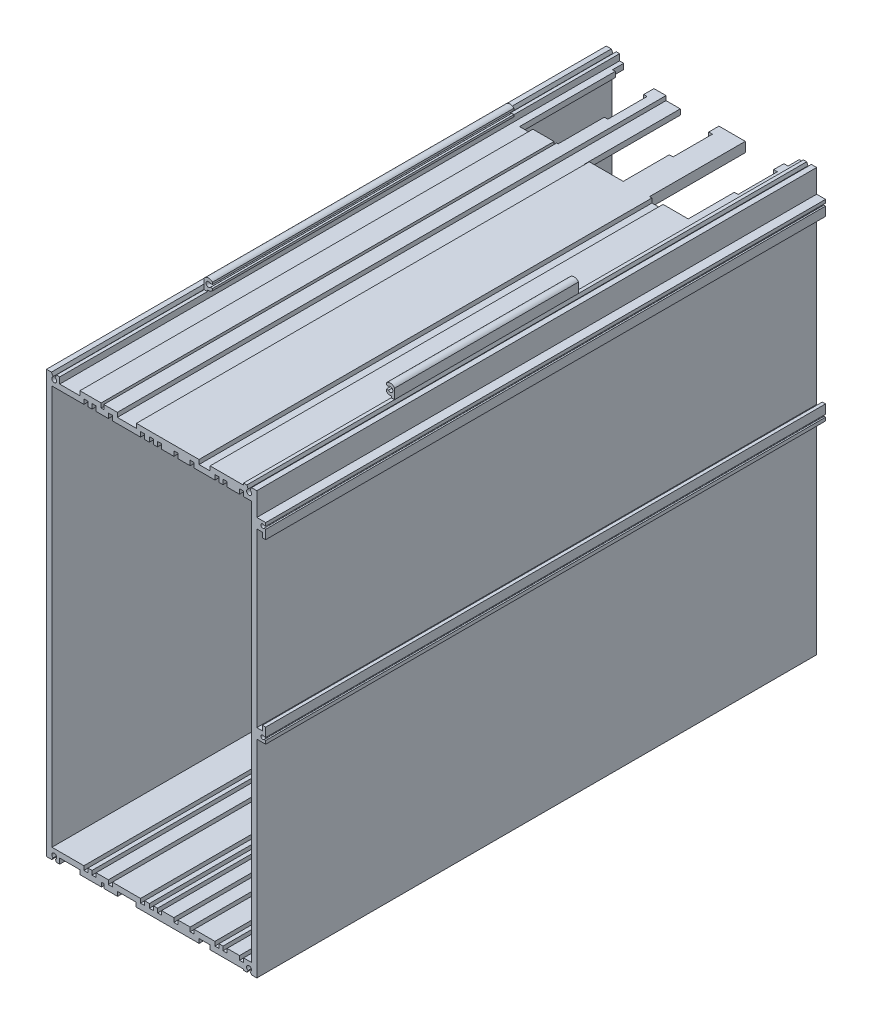
SolidWorks part; units mm, degrees
ref_plane "Front Plane" through (0, 0, 0) normal (0, 0, 1) x (1, 0, 0)
ref_plane "Top Plane" through (0, 0, 0) normal (0, 1, 0) x (1, 0, 0)
ref_plane "Right Plane" through (0, 0, 0) normal (1, 0, 0) x (0, 0, -1)
sketch "Sketch2" plane through (0, 0, 0) normal (0, 0, 1) x (1, 0, 0)
  line L0 (23.2732, 131.1707) -> (119.1108, 131.6725) construction
  line L1 (14.5, 261.3734) -> (14.5, 257.5858)
  line L2 (14.5, 257.5858) -> (26.7, 257.5858)
  line L3 (26.7, 257.5858) -> (26.7, 260.24)
  line L4 (26.7, 260.24) -> (39.5, 260.24)
  line L5 (39.5, 260.24) -> (39.5, 257.5858)
  line L6 (39.5, 257.5858) -> (41.1, 257.5858)
  line L7 (41.1, 257.5858) -> (41.1, 260.24)
  line L8 (41.1, 260.24) -> (49.3, 260.24)
  line L9 (49.3, 260.24) -> (49.3, 257.5858)
  line L10 (49.3, 257.5858) -> (60.8, 257.5858)
  line L11 (60.8, 257.5858) -> (60.8, 260.24)
  line L12 (60.8, 260.24) -> (98.6, 260.24)
  line L13 (98.6, 260.24) -> (98.6, 257.5858)
  line L14 (98.6, 257.5858) -> (105.3, 257.5858)
  line L15 (105.3, 257.5858) -> (105.3, 260.24)
  line L16 (105.3, 260.24) -> (125.5, 260.24)
  line L17 (125.5, 260.24) -> (125.5, 261.3734)
  line L18 (125.5, 261.3734) -> (127.5, 261.3734)
  line L19 (133.5, 261.3734) -> (133.5, 247.3734)
  line L20 (133.5, 247.3734) -> (138.85, 247.3734)
  line L21 (138.85, 247.3734) -> (138.85, 238.4234)
  line L22 (138.85, 238.4234) -> (136.9, 238.4234)
  line L23 (136.9, 238.4234) -> (136.9, 241.3734)
  line L24 (136.9, 241.3734) -> (133.5, 241.3734)
  line L25 (133.5, 241.3734) -> (133.5, 137.4734)
  line L26 (133.5, 137.4734) -> (136.9, 137.4734)
  line L27 (136.9, 137.4734) -> (136.9, 140.4234)
  line L28 (136.9, 140.4234) -> (138.85, 140.4234)
  line L29 (138.85, 140.4234) -> (138.85, 131.4734)
  line L30 (138.85, 131.4734) -> (133.5, 131.4734)
  line L31 (133.5, 131.4734) -> (133.5, 6.5734)
  line L32 (133.5, 6.5734) -> (130.3, 6.5734)
  line L33 (125.5, 6.5734) -> (125.5, 7.202)
  line L34 (125.5, 7.202) -> (105.25, 7.202)
  line L35 (105.25, 7.202) -> (105.25, 9.7858)
  line L36 (105.25, 9.7858) -> (98.65, 9.7858)
  line L37 (98.65, 9.7858) -> (98.65, 7.202)
  line L38 (98.65, 7.202) -> (60.55, 7.202)
  line L39 (60.55, 7.202) -> (60.55, 9.7858)
  line L40 (60.55, 9.7858) -> (49.45, 9.7858)
  line L41 (49.45, 9.7858) -> (49.45, 7.202)
  line L42 (49.45, 7.202) -> (41.2, 7.202)
  line L43 (41.2, 7.202) -> (41.2, 9.7858)
  line L44 (41.2, 9.7858) -> (39.6964, 9.7858)
  line L45 (39.6964, 9.7858) -> (39.6964, 7.202)
  line L46 (39.6964, 7.202) -> (26.5964, 7.202)
  line L47 (26.5964, 7.202) -> (26.5964, 9.7858)
  line L48 (26.5964, 9.7858) -> (14.4964, 9.7858)
  line L49 (14.4964, 9.7858) -> (14.4964, 6.5734)
  line L50 (14.4964, 6.5734) -> (12.4964, 6.5734)
  line L51 (6.5, 6.5734) -> (6.5, 261.3734)
  line L52 (6.5, 261.3734) -> (9.5, 261.3734)
  line L53 (9.8, 254.2858) -> (29.1, 254.2858)
  line L54 (29.1, 254.2858) -> (29.1, 257.1858)
  line L55 (29.1, 257.1858) -> (31.55, 257.1858)
  line L56 (31.55, 257.1858) -> (31.55, 254.2858)
  line L57 (31.55, 254.2858) -> (34, 254.2858)
  line L58 (34, 254.2858) -> (34, 257.1858)
  line L59 (34, 257.1858) -> (36.45, 257.1858)
  line L60 (36.45, 257.1858) -> (36.45, 254.2858)
  line L61 (36.45, 254.2858) -> (43.85, 254.2858)
  line L62 (43.85, 254.2858) -> (43.85, 257.1858)
  line L63 (43.85, 257.1858) -> (46.3, 257.1858)
  line L64 (46.3, 257.1858) -> (46.3, 254.2858)
  line L65 (46.3, 254.2858) -> (63.3, 254.2858)
  line L66 (63.3, 254.2858) -> (63.3, 257.1858)
  line L67 (63.3, 257.1858) -> (65.75, 257.1858)
  line L68 (65.75, 257.1858) -> (65.75, 254.2858)
  line L69 (65.75, 254.2858) -> (68.65, 254.2858)
  line L70 (68.65, 254.2858) -> (68.65, 257.1858)
  line L71 (68.65, 257.1858) -> (71.1, 257.1858)
  line L72 (71.1, 257.1858) -> (71.1, 254.2858)
  line L73 (71.1, 254.2858) -> (73.55, 254.2858)
  line L74 (73.55, 254.2858) -> (73.55, 257.1858)
  line L75 (73.55, 257.1858) -> (76, 257.1858)
  line L76 (76, 257.1858) -> (76, 254.2858)
  line L77 (76, 254.2858) -> (83.4, 254.2858)
  line L78 (83.4, 254.2858) -> (83.4, 257.1858)
  line L79 (83.4, 257.1858) -> (85.85, 257.1858)
  line L80 (85.85, 257.1858) -> (85.85, 254.2858)
  line L81 (85.85, 254.2858) -> (93.25, 254.2858)
  line L82 (93.25, 254.2858) -> (93.25, 257.1858)
  line L83 (93.25, 257.1858) -> (95.7, 257.1858)
  line L84 (95.7, 257.1858) -> (95.7, 254.2858)
  line L85 (95.7, 254.2858) -> (108.2, 254.2858)
  line L86 (108.2, 254.2858) -> (108.2, 257.1858)
  line L87 (108.2, 257.1858) -> (110.65, 257.1858)
  line L88 (110.65, 257.1858) -> (110.65, 254.2858)
  line L89 (110.65, 254.2858) -> (113.1, 254.2858)
  line L90 (113.1, 254.2858) -> (113.1, 257.1858)
  line L91 (113.1, 257.1858) -> (115.55, 257.1858)
  line L92 (115.55, 257.1858) -> (115.55, 254.2858)
  line L93 (115.55, 254.2858) -> (123.05, 254.2858)
  line L94 (123.05, 254.2858) -> (123.05, 257.1858)
  line L95 (123.05, 257.1858) -> (125.5, 257.1858)
  line L96 (125.5, 257.1858) -> (125.5, 254.2858)
  line L97 (125.5, 254.2858) -> (130.2, 254.2858)
  line L98 (130.2, 254.2858) -> (130.2, 13.0858)
  line L99 (130.2, 13.0858) -> (125.5, 13.0858)
  line L100 (125.5, 13.0858) -> (125.5, 10.6056)
  line L101 (125.5, 10.6056) -> (123.05, 10.6056)
  line L102 (123.05, 10.6056) -> (123.05, 13.0858)
  line L103 (123.05, 13.0858) -> (115.55, 13.0858)
  line L104 (115.55, 13.0858) -> (115.55, 10.6056)
  line L105 (115.55, 10.6056) -> (113.1, 10.6056)
  line L106 (113.1, 10.6056) -> (113.1, 13.0858)
  line L107 (113.1, 13.0858) -> (110.65, 13.0858)
  line L108 (110.65, 13.0858) -> (110.65, 10.6056)
  line L109 (110.65, 10.6056) -> (108.2, 10.6056)
  line L110 (108.2, 10.6056) -> (108.2, 13.0858)
  line L111 (108.2, 13.0858) -> (95.7, 13.0858)
  line L112 (95.7, 13.0858) -> (95.7, 10.6056)
  line L113 (95.7, 10.6056) -> (93.25, 10.6056)
  line L114 (93.25, 10.6056) -> (93.25, 13.0858)
  line L115 (93.25, 13.0858) -> (85.85, 13.0858)
  line L116 (85.85, 13.0858) -> (85.85, 10.6056)
  line L117 (85.85, 10.6056) -> (83.4, 10.6056)
  line L118 (83.4, 10.6056) -> (83.4, 13.0858)
  line L119 (83.4, 13.0858) -> (76, 13.0858)
  line L120 (76, 13.0858) -> (76, 10.6056)
  line L121 (76, 10.6056) -> (73.55, 10.6056)
  line L122 (73.55, 10.6056) -> (73.55, 13.0858)
  line L123 (73.55, 13.0858) -> (71.1, 13.0858)
  line L124 (71.1, 13.0858) -> (71.1, 10.6056)
  line L125 (71.1, 10.6056) -> (68.65, 10.6056)
  line L126 (68.65, 10.6056) -> (68.65, 13.0858)
  line L127 (68.65, 13.0858) -> (65.75, 13.0858)
  line L128 (65.75, 13.0858) -> (65.75, 10.6056)
  line L129 (65.75, 10.6056) -> (63.3, 10.6056)
  line L130 (63.3, 10.6056) -> (63.3, 13.0858)
  line L131 (63.3, 13.0858) -> (46.3, 13.0858)
  line L132 (46.3, 13.0858) -> (46.3, 10.6056)
  line L133 (46.3, 10.6056) -> (43.85, 10.6056)
  line L134 (43.85, 10.6056) -> (43.85, 13.0858)
  line L135 (43.85, 13.0858) -> (36.45, 13.0858)
  line L136 (36.45, 13.0858) -> (36.45, 10.6056)
  line L137 (36.45, 10.6056) -> (34, 10.6056)
  line L138 (34, 10.6056) -> (34, 13.0858)
  line L139 (34, 13.0858) -> (31.55, 13.0858)
  line L140 (31.55, 13.0858) -> (31.55, 10.6056)
  line L141 (31.55, 10.6056) -> (29.1, 10.6056)
  line L142 (29.1, 10.6056) -> (29.1, 13.0858)
  line L143 (29.1, 13.0858) -> (9.8, 13.0858)
  line L144 (9.8, 13.0858) -> (9.8, 254.2858)
  line L145 (11.2, 258.1858) -> (12.5, 261.3734)
  line L146 (11.2, 258.1858) -> (9.5, 261.3734)
  line L147 (12.5, 261.3734) -> (14.5, 261.3734)
  line L148 (128.8, 258.1858) -> (127.5, 261.3734)
  line L149 (128.8, 258.1858) -> (130.3, 261.3734)
  line L150 (130.3, 261.3734) -> (133.5, 261.3734)
  line L151 (138.85, 245.3734) -> (137.9352, 245.3734)
  line L152 (138.85, 243.8734) -> (137.8905, 243.8734)
  line L153 (138.85, 133.4734) -> (137.9352, 133.4734)
  line L154 (138.85, 134.9734) -> (137.8905, 134.9734)
  line L155 (128.8, 9.1858) -> (130.3, 6.5734)
  line L156 (128.8, 9.1858) -> (127.5, 6.5734)
  line L157 (127.5, 6.5734) -> (125.5, 6.5734)
  line L158 (11.2, 9.1858) -> (12.4964, 6.5734)
  line L159 (11.2, 9.1858) -> (9.7, 6.5734)
  line L160 (9.7, 6.5734) -> (6.5, 6.5734)
  circle A1 centre (11.2, 258.1858) radius 1.5
  circle A2 centre (128.8, 258.1858) radius 1.5
  circle A3 centre (137.075, 244.6484) radius 1.125
  circle A4 centre (137.075, 134.1984) radius 1.125
  circle A5 centre (128.8, 9.1858) radius 1.5
  circle A6 centre (11.2, 9.1858) radius 1.5
  point P51 (54.8, 13.0858)
  dimension "D1" = 127
  dimension "D87" = 3.2
  dimension "D90" = 3
  dimension "D92" = 2.4
  dimension "D93" = 3
  dimension "D97" = 5.75
  dimension "D101" = 5.75
  dimension "D106" = 3
  dimension "D111" = 3
  dimension "D2" = 3.3
  dimension "D3" = 3.3
  dimension "D4" = 120.4
  dimension "D5" = 8
  dimension "D6" = 8
  dimension "D7" = 3.3
  dimension "D8" = 3.3
  dimension "D9" = 254.8
  dimension "D10" = 247.8
  dimension "D11" = 241.2
  dimension "D12" = 12.2
  dimension "D13" = 12.8
  dimension "D14" = 1.6
  dimension "D15" = 37.8
  dimension "D16" = 8.2
  dimension "D17" = 11.5
  dimension "D18" = 6.7
  dimension "D19" = 20.2
  dimension "D20" = 19.3
  dimension "D21" = 2.9
  dimension "D22" = 2.45
  dimension "D23" = 2.45
  dimension "D24" = 2.45
  dimension "D25" = 2.45
  dimension "D26" = 2.45
  dimension "D27" = 2.45
  dimension "D28" = 2.45
  dimension "D29" = 2.45
  dimension "D30" = 2.45
  dimension "D31" = 2.45
  dimension "D32" = 2.45
  dimension "D33" = 2.45
  dimension "D34" = 7.4
  dimension "D35" = 17
  dimension "D36" = 19.3
  dimension "D37" = 2.9
  dimension "D38" = 2.45
  dimension "D39" = 7.4
  dimension "D40" = 7.4
  dimension "D41" = 12.5
  dimension "D42" = 2.45
  dimension "D43" = 7.5
  dimension "D44" = 4.7
  dimension "D45" = 2.45
  dimension "D46" = 2.45
  dimension "D47" = 2.45
  dimension "D48" = 7.4
  dimension "D49" = 2.45
  dimension "D50" = 17
  dimension "D51" = 2.45
  dimension "D52" = 2.9
  dimension "D53" = 2.45
  dimension "D54" = 2.45
  dimension "D55" = 2.45
  dimension "D56" = 7.4
  dimension "D57" = 2.45
  dimension "D58" = 7.4
  dimension "D59" = 2.45
  dimension "D60" = 12.5
  dimension "D61" = 2.45
  dimension "D62" = 2.45
  dimension "D63" = 2.45
  dimension "D64" = 7.5
  dimension "D65" = 2.45
  dimension "D66" = 4.7
  dimension "D67" = 7.9964
  dimension "D68" = 12.1
  dimension "D69" = 13.1
  dimension "D70" = 8.25
  dimension "D71" = 11.1
  dimension "D72" = 38.1
  dimension "D73" = 6.6
  dimension "D74" = 20.25
  dimension "D75" = 8
  dimension "D76" = 14
  dimension "D77" = 6
  dimension "D78" = 8.95
  dimension "D79" = 3.4
  dimension "D80" = 1.95
  dimension "D81" = 6
  dimension "D82" = 8.95
  dimension "D83" = 3.4
  dimension "D84" = 1.95
  dimension "D85" = 5.35
  dimension "D86" = 103.9
  dimension "D88" = 2.4
  dimension "D89" = 3
  dimension "D91" = 2
  dimension "D94" = 3.2
  dimension "D95" = 2
  dimension "D96" = 3.2
  dimension "D98" = 1.6
  dimension "D99" = 2
  dimension "D100" = 5.45
  dimension "D102" = 1.6
  dimension "D103" = 2
  dimension "D104" = 5.45
  dimension "D105" = 1.5
  dimension "D107" = 2.4
  dimension "D108" = 3.2
  dimension "D109" = 2
  dimension "D110" = 3.2
  dimension "D112" = 2.4
  dimension "D113" = 3.2
  dimension "D114" = 3.2
  dimension "D115" = 2
extrude "Boss-Extrude1" add sketch "Sketch2" along normal blind 338 contours A6 L158 L50 L49 L48 L47 L46 L45 L44 L43 L42 L41 L40 L39 L38 L37 L36 L35 L34 L33 L157 L156 A5 L155 L32 L31 L30 L29 L153 A4 L154 L28 L27 L26 L25 L24 L23 L22 L21 L152 A3 L151 L20 L19 L150 L149 A2 L148 L18
ref_plane "Plane1" through (0, 0, 60) normal (0, 0, -1) x (-1, 0, 0)
sketch "Sketch3" plane through (0, 0, 60) normal (0, 0, -1) x (-1, 0, 0)
  line L0 (-127.5, 261.3734) -> (-127.5, 267.3734)
  line L1 (-122.5, 270.1784) -> (-122.5, 262.1784)
  line L2 (-125.5, 261.3734) -> (-125.5, 269.0865)
  line L3 (-121.7757, 266.54) -> (-123.9222, 266.54)
  line L4 (-121.7757, 264.44) -> (-123.7503, 264.44)
  line L5 (-133.5, 251.3903) -> (-6.5, 251.3903) construction
  line L6 (-133.5, 261.3734) -> (-133.5, 247.3734) construction
  line L7 (-6.5, 6.5734) -> (-6.5, 261.3734) construction
  line L8 (-105.3, 260.24) -> (-125.5, 260.24) construction
  line L10 (-70, 251.3903) -> (-70, 270.1784) construction
  line L11 (-14.5, 261.3734) -> (-14.5, 269.0865)
  line L12 (-12.5, 261.3734) -> (-12.5, 267.3734)
  line L13 (-18.2243, 264.44) -> (-16.2497, 264.44)
  line L14 (-18.2243, 266.54) -> (-16.0778, 266.54)
  line L15 (-17.5, 270.1784) -> (-17.5, 262.1784)
  line L16 (-127.5, 261.3734) -> (-125.5, 261.3734)
  line L17 (-14.5, 261.3734) -> (-12.5, 261.3734)
  circle A0 centre (-124.8514, 265.49) radius 3.25
  circle A2 centre (-124.9004, 265.4028) radius 1.5
  circle A6 centre (-15.0996, 265.4028) radius 1.5
  circle A7 centre (-15.1486, 265.49) radius 3.25
  dimension "D1" = 6.5
  dimension "D5" = 3
  dimension "D6" = 1.85
  dimension "D2" = 5
  dimension "D3" = 6
  dimension "D4" = 2
  dimension "D7" = 2.2
  dimension "D8" = 2.2
extrude "Boss-Extrude2" add sketch "Sketch3" against normal blind 188.8 contours A7 L11 A6 L13 L15 | A7 L12 L11 A6 | L12 A7 L11 L17 | A7 L15 L14 A6 L11 | A0 L0 L16 L2 | A2 L2 A0 L0 | A2 L3 L1 A0 L2 | A2 L2 A0 L1 L4
sketch "Sketch4" plane through (127.5, 0, 0) normal (1, 0, 0) x (0, 0, -1)
  line L0 (-248.8, 261.3734) -> (-248.8, 267.3734) construction
  line L5 (-60, 261.3734) -> (-137.8, 261.3734)
  line L6 (-60, 261.3734) -> (-60, 282.1971)
  line L7 (-60, 282.1971) -> (-137.8, 282.1971)
  line L8 (-137.8, 261.3734) -> (-137.8, 282.1971)
  line L9 (-60, 261.3734) -> (-137.8, 282.1971) construction
  line L10 (-60, 282.1971) -> (-137.8, 261.3734) construction
  point P4 (-98.9, 271.7852)
  dimension "D1" = 111
extrude "Cut-Extrude3" cut sketch "Sketch4" against normal up to next
sketch "Sketch5" plane through (0, 260.24, 0) normal (0, 1, 0) x (1, 0, 0)
  line L0 (105.3, 0) -> (125.5, 0) construction
  line L1 (17, -6.75) -> (123, -6.75)
  line L2 (17, -6.75) -> (17, 0)
  line L3 (17, 0) -> (123, 0)
  line L4 (123, -6.75) -> (123, 0)
  line L5 (17, -6.75) -> (123, 0) construction
  line L6 (17, 0) -> (123, -6.75) construction
  line L7 (14.5, -60) -> (14.5, 0) construction
  line L8 (125.5, -137.8) -> (125.5, 0) construction
  point P4 (70, -3.375)
  dimension "D1" = 106
  dimension "D2" = 2.5
  dimension "D3" = 6.75
  dimension "D4" = 2.5
extrude "Cut-Extrude4" cut sketch "Sketch5" against normal up to next
sketch "Sketch6" plane through (0, 260.24, 0) normal (0, 1, 0) x (1, 0, 0)
  line L0 (105.3, -6.75) -> (123, -6.75) construction
  line L1 (120.5, -6.75) -> (97.15, -6.75)
  line L2 (120.5, -6.75) -> (120.5, -64.55)
  line L3 (120.5, -64.55) -> (97.15, -64.55)
  line L4 (97.15, -6.75) -> (97.15, -64.55)
  line L5 (120.5, -6.75) -> (97.15, -64.55) construction
  line L6 (120.5, -64.55) -> (97.15, -6.75) construction
  line L7 (125.5, -338) -> (125.5, 0) construction
  line L8 (133.5, 0) -> (138.85, 0) construction
  line L9 (60.8, -6.75) -> (98.6, -6.75) construction
  line L10 (81.25, -6.75) -> (57.9, -6.75)
  line L11 (81.25, -6.75) -> (81.25, -64.55)
  line L12 (81.25, -64.55) -> (57.9, -64.55)
  line L13 (57.9, -6.75) -> (57.9, -64.55)
  line L14 (81.25, -6.75) -> (57.9, -64.55) construction
  line L15 (81.25, -64.55) -> (57.9, -6.75) construction
  line L16 (60.8, -6.75) -> (49.3, -6.75) construction
  line L17 (42, -6.75) -> (18.65, -6.75)
  line L18 (42, -6.75) -> (42, -64.55)
  line L19 (42, -64.55) -> (18.65, -64.55)
  line L20 (18.65, -6.75) -> (18.65, -64.55)
  line L21 (42, -6.75) -> (18.65, -64.55) construction
  line L22 (42, -64.55) -> (18.65, -6.75) construction
  point P4 (108.825, -35.65)
  point P15 (69.575, -35.65)
  point P22 (30.325, -35.65)
  dimension "D1" = 23.35
  dimension "D2" = 5
  dimension "D3" = 57.8
  dimension "D4" = 64.55
  dimension "D5" = 57.8
  dimension "D6" = 15.9
  dimension "D7" = 23.35
  dimension "D8" = 23.35
  dimension "D9" = 15.9
extrude "Cut-Extrude5" cut sketch "Sketch6" against normal up to next
sketch "Sketch7" plane through (12.5, 0, 0) normal (-1, 0, 0) x (0, 0, 1)
  line L1 (0, 261.3734) -> (66.8, 261.3734)
  line L2 (0, 261.3734) -> (0, 273.0065)
  line L3 (0, 273.0065) -> (66.8, 273.0065)
  line L4 (66.8, 261.3734) -> (66.8, 273.0065)
  line L5 (0, 261.3734) -> (66.8, 273.0065) construction
  line L6 (0, 273.0065) -> (66.8, 261.3734) construction
  point P4 (33.4, 267.19)
  dimension "D1" = 66.8
extrude "Cut-Extrude6" cut sketch "Sketch7" against normal up to next
sketch "Sketch8" plane through (0, 260.24, 0) normal (0, 1, 0) x (1, 0, 0)
  line L0 (120.5, -64.55) -> (120.5, -6.75) construction
  line L1 (120.5, -12.95) -> (122.75, -12.95)
  line L2 (120.5, -12.95) -> (120.5, -36.7)
  line L3 (120.5, -36.7) -> (122.75, -36.7)
  line L4 (122.75, -12.95) -> (122.75, -36.7)
  line L5 (120.5, -12.95) -> (122.75, -36.7) construction
  line L6 (120.5, -36.7) -> (122.75, -12.95) construction
  line L7 (120.5, -6.75) -> (123, -6.75) construction
  line L8 (81.25, -64.55) -> (81.25, -6.75) construction
  line L9 (81.25, -12.95) -> (83.5, -12.95)
  line L10 (81.25, -12.95) -> (81.25, -36.7)
  line L11 (81.25, -36.7) -> (83.5, -36.7)
  line L12 (83.5, -12.95) -> (83.5, -36.7)
  line L13 (81.25, -12.95) -> (83.5, -36.7) construction
  line L14 (81.25, -36.7) -> (83.5, -12.95) construction
  line L16 (41.8337, -12.95) -> (44.0837, -12.95)
  line L17 (41.8337, -12.95) -> (41.8337, -36.7)
  line L18 (41.8337, -36.7) -> (44.0837, -36.7)
  line L19 (44.0837, -12.95) -> (44.0837, -36.7)
  line L20 (41.8337, -12.95) -> (44.0837, -36.7) construction
  line L21 (41.8337, -36.7) -> (44.0837, -12.95) construction
  point P4 (121.625, -24.825)
  point P13 (82.375, -24.825)
  point P20 (42.9587, -24.825)
  dimension "D1" = 6.2
  dimension "D2" = 23.75
  dimension "D3" = 2.25
  dimension "D4" = 2.25
  dimension "D5" = 2.25
extrude "Cut-Extrude7" cut sketch "Sketch8" against normal up to next
